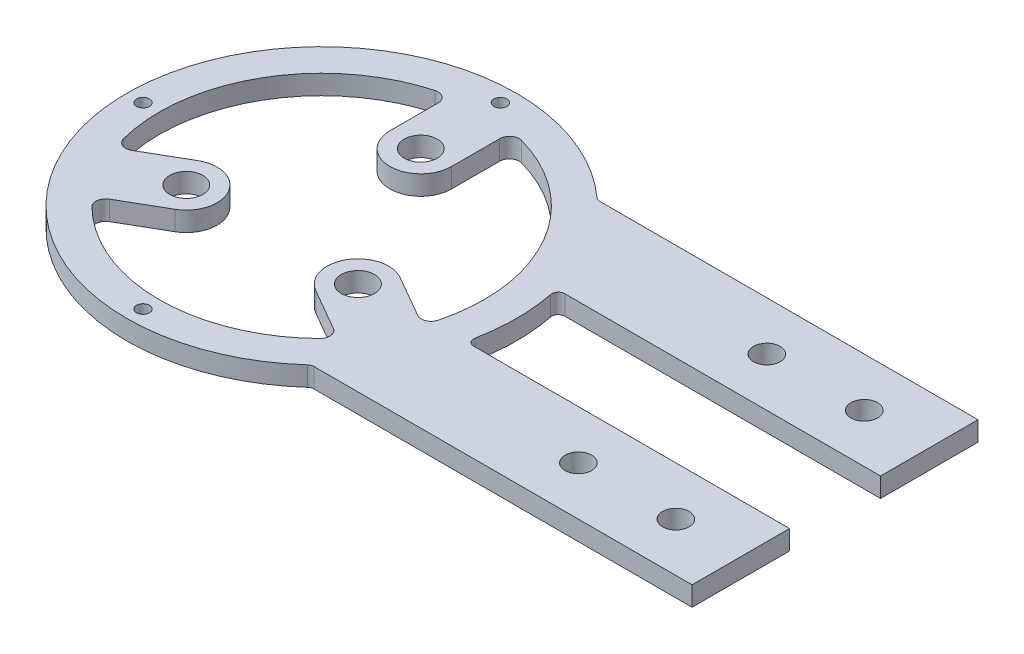
SolidWorks part; units mm, degrees
ref_plane "Front Plane" through (0, 0, 0) normal (0, 0, 1) x (1, 0, 0)
ref_plane "Top Plane" through (0, 0, 0) normal (0, 1, 0) x (1, 0, 0)
ref_plane "Right Plane" through (0, 0, 0) normal (1, 0, 0) x (0, 0, -1)
sketch "Sketch1" plane through (0, 0, 0) normal (0, 1, 0) x (1, 0, 0)
  circle A0 centre (0, 0) radius 30
  circle A4 centre (0, 0) radius 25
  dimension "D1" = 60
  dimension "D2" = 5
extrude "Boss-Extrude1" add sketch "Sketch1" along normal blind 3
sketch "Sketch2" plane through (0, 3, 0) normal (0, 1, 0) x (1, 0, 0)
  line L0 (-4.75, 15.25) -> (-4.75, 24.5446)
  line L1 (4.75, 15.25) -> (4.75, 24.5446)
  circle A0 centre (0, 0) radius 15.25 construction
  circle A1 centre (0, 15.25) radius 2.55
  arc A2 (-4.75, 15.25) -> (4.75, 15.25) centre (0, 15.25) ccw
  circle A3 centre (0, 0) radius 25 construction
  arc A4 (-4.75, 24.5446) -> (4.75, 24.5446) centre (0, 0) cw
  dimension "D1" = 30.5
  dimension "D2" = 5.1
  dimension "D3" = 2.2
extrude "Boss-Extrude2" add sketch "Sketch2" against normal up to surface (3 mm away) up to face at (0, 0, 30)
pattern_circular "CirPattern1" count 3 over 360 about axis through (0, 0, 0) along (0, 1, 0) of "Boss-Extrude2"
fillet "Fillet1" radius 1.5 6 edges at (23.6312, 1.5, 8.1587) (18.8812, 1.5, 16.3859) (-23.6312, 1.5, 8.1587) (-18.8812, 1.5, 16.3859) (4.75, 1.5, -24.5446) (-4.75, 1.5, -24.5446)
sketch "Sketch3" plane through (0, 3, 0) normal (0, 1, 0) x (1, 0, 0)
  line L1 (20.3961, 22) -> (79, 22)
  line L3 (29.1719, 7) -> (79, 7)
  line L4 (79, 22) -> (79, 7)
  line L5 (29.1719, -7) -> (79, -7)
  line L7 (20.3961, -22) -> (79, -22)
  line L8 (79, -7) -> (79, -22)
  line L9 (19.2614, 23) -> (80, 23) construction
  line L11 (29.3939, 6) -> (80, 6) construction
  line L12 (80, 23) -> (80, 6) construction
  line L13 (29.3939, -6) -> (80, -6) construction
  line L15 (19.2614, -23) -> (80, -23) construction
  line L16 (80, -6) -> (80, -23) construction
  circle A0 centre (0, 0) radius 30 construction
  arc A1 (19.2614, 23) -> (29.3939, 6) centre (0, 0) cw construction
  arc A2 (29.3939, -6) -> (19.2614, -23) centre (0, 0) cw construction
  arc A3 (20.3961, 22) -> (29.1719, 7) centre (0, 0) cw
  arc A4 (29.1719, -7) -> (20.3961, -22) centre (0, 0) cw
  dimension "D1" = 12
  dimension "D2" = 80
  dimension "D3" = 6
  dimension "D4" = 17
  dimension "D5" = 1
  dimension "D6" = 1
  dimension "D7" = 1
  dimension "D8" = 1
  dimension "D9" = 1
extrude "Boss-Extrude3" add sketch "Sketch3" against normal up to surface (3 mm away) up to face at (0, 0, 30)
sketch "Sketch4" plane through (0, 3, 0) normal (0, 1, 0) x (1, 0, 0)
  line L0 (79, 7) -> (79, 22) construction
  line L1 (54, 14.5) -> (69, 14.5) construction
  line L2 (54, 14.5) -> (54, -14.5) construction
  line L3 (54, -14.5) -> (69, -14.5) construction
  line L4 (69, 14.5) -> (69, -14.5) construction
  line L5 (79, -22) -> (79, -7) construction
  circle A0 centre (54, 14.5) radius 2.05
  circle A1 centre (69, 14.5) radius 2.05
  circle A2 centre (54, -14.5) radius 2.05
  circle A3 centre (69, -14.5) radius 2.05
  point P10 (79, 14.5)
  point P13 (79, -14.5)
  dimension "D1" = 4.1
  dimension "D2" = 15
  dimension "D3" = 10
extrude "Cut-Extrude1" cut sketch "Sketch4" against normal through all
sketch "Sketch5" plane through (0, 3, 0) normal (0, 1, 0) x (1, 0, 0)
  circle A0 centre (0, 0) radius 27.5 construction
  circle A1 centre (0, 27.5) radius 1
  circle A2 centre (-27.5, 0) radius 1
  circle A3 centre (0, -27.5) radius 1
  dimension "D1" = 2
  dimension "D2" = 55
extrude "Cut-Extrude2" cut sketch "Sketch5" against normal through all
fillet "Fillet2" radius 1 4 edges at (29.1719, 1.5, 7) (29.1719, 1.5, -7) (20.3961, 1.5, -22) (20.3961, 1.5, 22)
